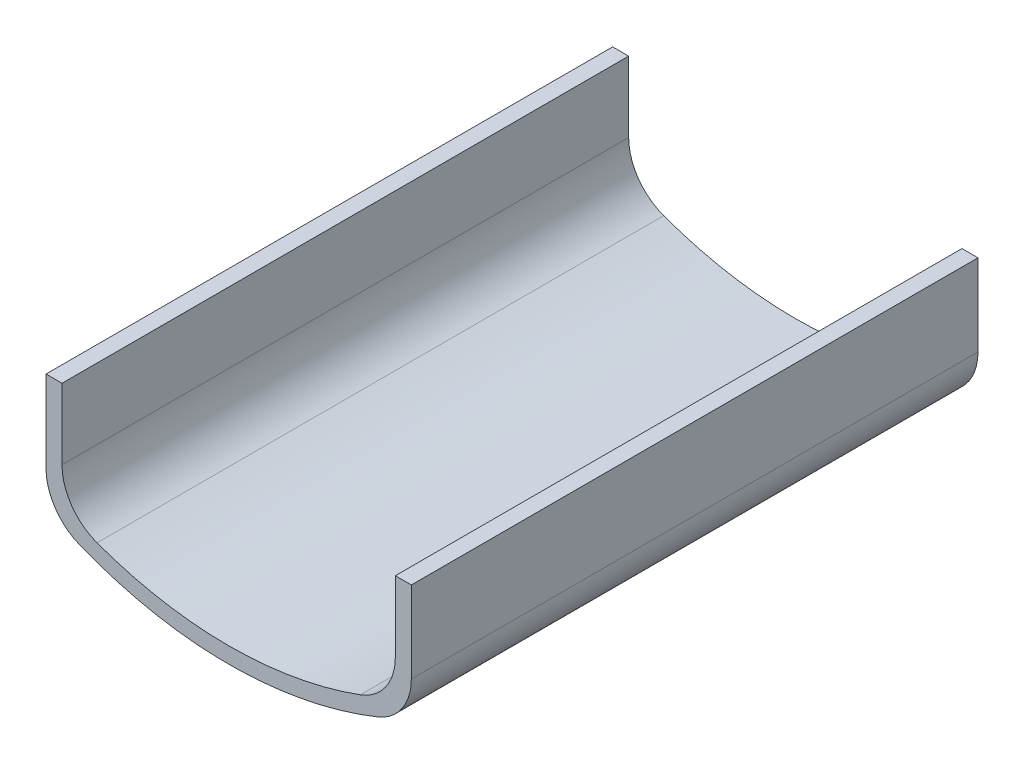
SolidWorks part; units mm, degrees
ref_plane "Front Plane" through (0, 0, 0) normal (0, 0, 1) x (1, 0, 0)
ref_plane "Top Plane" through (0, 0, 0) normal (0, 1, 0) x (1, 0, 0)
ref_plane "Right Plane" through (0, 0, 0) normal (1, 0, 0) x (0, 0, -1)
sketch "Sketch3" plane through (0, 0, 0) normal (0, 0, 1) x (1, 0, 0)
  line L0 (0, 0.453) -> (0, 7.0512) construction
  line L1 (7.9375, 5.041) -> (7.9375, 1.6801)
  line L2 (-7.9375, 5.041) -> (-7.9375, 1.6801)
  line L3 (7.9375, 5.041) -> (8.6995, 5.041)
  line L4 (8.6995, 5.041) -> (8.6995, 1.1566)
  line L5 (-8.6995, 5.041) -> (-8.6995, 1.1566)
  line L6 (-7.9375, 5.041) -> (-8.6995, 5.041)
  circle A0 centre (0, 16.4404) radius 13.8906 construction
  arc A1 (6.2698, -0.7054) -> (-6.2698, -0.7054) centre (0, 16.4404) cw
  arc A2 (7.1089, -1.1992) -> (-7.1089, -1.1992) centre (0, 16.4404) cw
  arc A3 (-7.1089, -1.1992) -> (-8.6995, 1.1566) centre (-6.1595, 1.1566) cw
  arc A4 (-7.9375, 1.6801) -> (-6.2698, -0.7054) centre (-5.3975, 1.6801) ccw
  arc A5 (7.9375, 1.6801) -> (6.2698, -0.7054) centre (5.3975, 1.6801) cw
  arc A6 (7.1089, -1.1992) -> (8.6995, 1.1566) centre (6.1595, 1.1566) ccw
  point P5 (0, 16.4404)
  point P18 (-7.9375, 0)
  point P21 (7.9375, 0)
  dimension "D2" = 27.7812
  dimension "D5" = 0.762
  dimension "D6" = 2.54
  dimension "D1" = 15.875
  dimension "D3" = 18.2562
  dimension "D4" = 0.762
extrude "Boss-Extrude1" add sketch "Sketch3" along normal blind 26.9875 contours A2 A3 L5 L6 L2 A4 A1 A5 L1 L3 L4 A6
